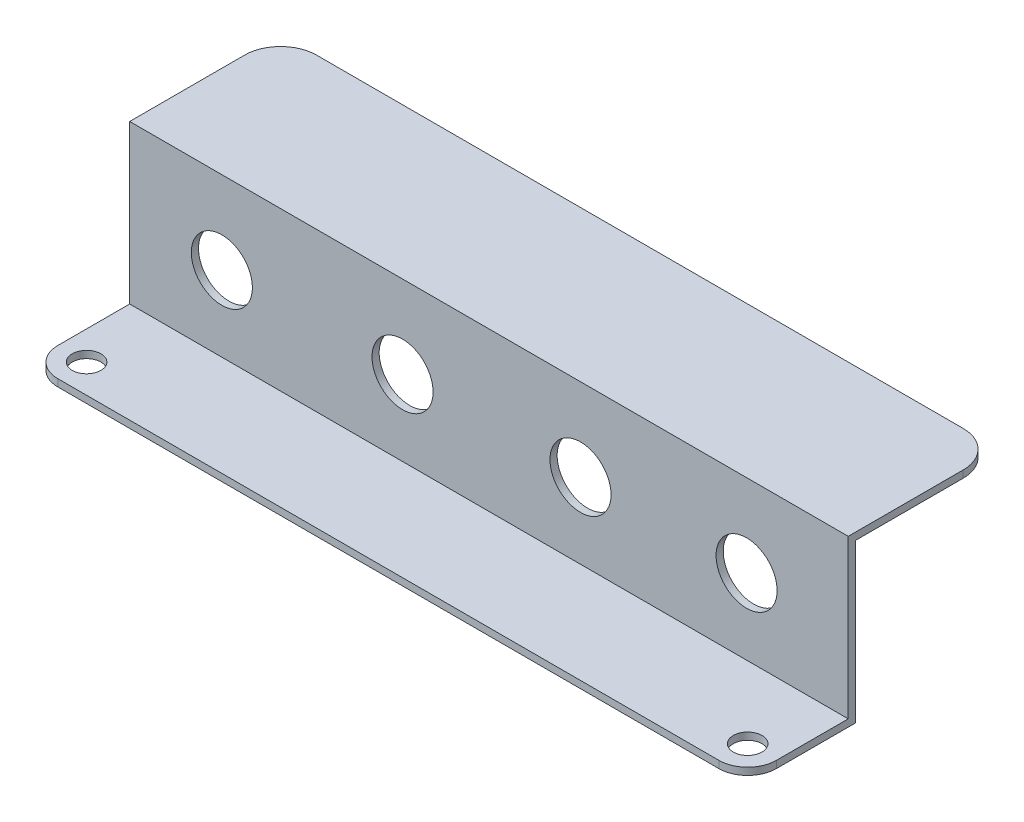
SolidWorks part; units mm, degrees
ref_plane "Front Plane" through (0, 0, 0) normal (0, 0, 1) x (1, 0, 0)
ref_plane "Top Plane" through (0, 0, 0) normal (0, 1, 0) x (1, 0, 0)
ref_plane "Right Plane" through (0, 0, 0) normal (1, 0, 0) x (0, 0, -1)
sketch "Sketch1" plane through (0, 0, 0) normal (0, 1, 0) x (1, 0, 0)
  line L1 (-50, -10) -> (50, -10)
  line L2 (-50, -10) -> (-50, 10)
  line L3 (-50, 10) -> (50, 10)
  line L4 (50, -10) -> (50, 10)
  line L5 (-50, -10) -> (50, 10) construction
  line L6 (-50, 10) -> (50, -10) construction
  point P0 (0, 0)
  dimension "D1" = 100
  dimension "D2" = 20
extrude "Boss-Extrude1" add sketch "Sketch1" along normal blind 1
sketch "Sketch3" plane through (0, 0, 10) normal (0, 0, 1) x (1, 0, 0)
  line L0 (50, 1) -> (50, 0) construction
  line L1 (-50, 1) -> (50, 1)
  line L2 (-50, 1) -> (-50, -22)
  line L3 (-50, -22) -> (50, -22)
  line L4 (50, 1) -> (50, -22)
  line L5 (-50, 1) -> (50, 1) construction
  dimension "D1" = 23
extrude "Boss-Extrude2" add sketch "Sketch3" along normal blind 1
sketch "Sketch4" plane through (0, -22, 0) normal (0, -1, 0) x (1, 0, 0)
  line L0 (50, 10) -> (50, -10) construction
  line L1 (-50, 11) -> (50, 11)
  line L2 (-50, 11) -> (-50, 25)
  line L3 (-50, 25) -> (50, 25)
  line L4 (50, 11) -> (50, 25)
  line L5 (50, 21) -> (46, 21) construction
  circle A1 centre (46, 21) radius 2
  circle A3 centre (-46, 21) radius 2
  dimension "D1" = 4
  dimension "D2" = 4
  dimension "D3" = 4
  dimension "D4" = 14
  dimension "D5" = 4
extrude "Boss-Extrude3" add sketch "Sketch4" against normal blind 1
fillet "Fillet1" radius 4 2 edges at (-50, -21.5, 25) (50, -21.5, 25)
sketch "Sketch5" plane through (0, -22, 0) normal (0, -1, 0) x (-1, 0, 0)
  line L0 (39.713, -14.1491) -> (39.713, -24.0551) construction
  line L1 (39.713, -24.0551) -> (34.633, -24.0551) construction
  line L2 (34.633, -24.0551) -> (34.633, -14.1491) construction
  line L3 (34.633, -14.1491) -> (14.5669, -14.1491) construction
  line L4 (14.5669, -14.1491) -> (14.5669, -24.0551) construction
  line L5 (14.5669, -24.0551) -> (9.4869, -24.0551) construction
  line L6 (9.4869, -24.0551) -> (9.4869, -14.1491) construction
  line L7 (9.4869, -14.1491) -> (7.9629, -14.1491) construction
  line L8 (7.9629, -14.1491) -> (-10.1981, -14.1491) construction
  line L9 (-10.1981, -14.1491) -> (-10.1981, -24.0551) construction
  line L10 (-10.1981, -24.0551) -> (-15.2781, -24.0551) construction
  line L11 (-15.2781, -24.0551) -> (-15.2781, -14.1491) construction
  line L12 (-15.2781, -14.1491) -> (-16.8021, -14.1491) construction
  line L13 (-16.8021, -14.1491) -> (-33.3122, -14.1491) construction
  line L14 (-33.3122, -14.1491) -> (-33.3122, -24.0551) construction
  line L15 (-33.3122, -24.0551) -> (-38.3922, -24.0551) construction
  line L16 (-38.3922, -24.0551) -> (-38.3922, -14.1491) construction
  line L17 (-38.3922, -14.1491) -> (-39.9162, -14.1491) construction
  line L18 (37.173, -24.0551) -> (37.173, -8.1491) construction
  line L19 (12.0269, -24.0551) -> (12.0269, -8.1491) construction
  line L20 (12.0269, -8.1491) -> (-12.7381, -24.0551) construction
  line L21 (-12.7381, -24.0551) -> (-12.7381, -8.1491) construction
  line L22 (-12.7381, -8.1491) -> (-35.8522, -24.0551) construction
  line L23 (-35.8522, -24.0551) -> (-35.8522, -8.1491) construction
sketch "Sketch6" plane through (0, 0, 11) normal (0, 0, 1) x (1, 0, 0)
  line L0 (-37.173, -22) -> (-37.173, -10.5) construction
  line L1 (-12.0269, -22) -> (-12.0269, -10.5) construction
  line L3 (12.7381, -22) -> (12.7381, -10.5) construction
  line L5 (35.8522, -22) -> (35.8522, -10.5) construction
  circle A0 centre (-37.173, -10.5) radius 4.25
  circle A1 centre (-12.0269, -10.5) radius 4.25
  circle A2 centre (12.7381, -10.5) radius 4.25
  circle A3 centre (35.8522, -10.5) radius 4.25
  dimension "D1" = 8.5
  dimension "D2" = 11.5
extrude "Cut-Extrude2" cut sketch "Sketch6" against normal up to next
fillet "Fillet2" radius 5 2 edges at (50, 0.5, -10) (-50, 0.5, -10)
